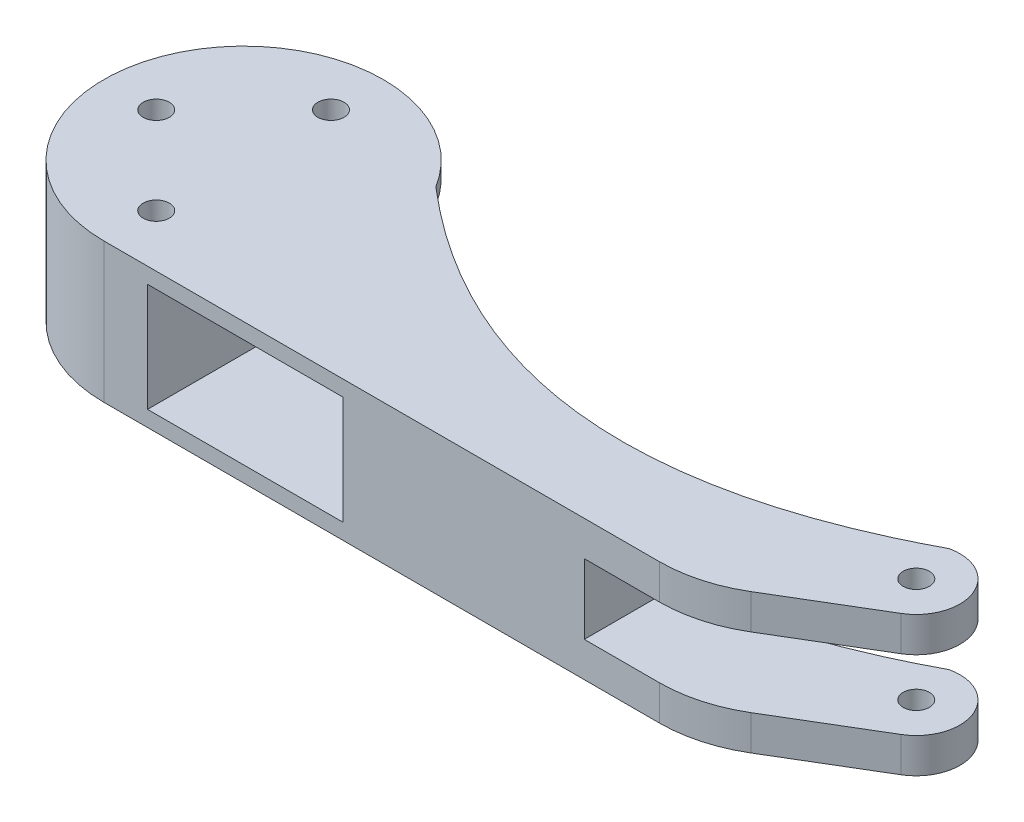
SolidWorks part; units mm, degrees
ref_plane "前视基准面" through (0, 0, 0) normal (0, 0, 1) x (1, 0, 0)
ref_plane "上视基准面" through (0, 0, 0) normal (0, 1, 0) x (1, 0, 0)
ref_plane "右视基准面" through (0, 0, 0) normal (1, 0, 0) x (0, 0, -1)
other "Configuration Table"
sketch "Sketch1" plane through (0, 0, 0) normal (0, 1, 0) x (1, 0, 0)
  line L0 (80, -3.5578) -> (80, -3)
  line L1 (0, -16) -> (80, -16)
  line L2 (80, -16) -> (80, -3)
  line L3 (45, -6) -> (45, -16)
  line L4 (45, -6) -> (7.5685, 14.0968)
  line L5 (45, -6) -> (78.8683, 1.8702)
  line L6 (68, -16) -> (82.5658, -7.2915)
  circle A0 centre (0, 0) radius 16
  circle A1 centre (80, -3) radius 1.5
  circle A2 centre (80, -3) radius 5
  spline S0 degree 2 poles (7.5685, 14.0968) (39.626, -19.032) (78.8683, 1.8702) knots 0 0 0 1 1 1
  point P9 (45, -6)
  point P12 (68, -16)
  dimension "D1" = 32
  dimension "D3" = 3
  dimension "D5" = 10
  dimension "D2" = 80
  dimension "D4" = 3
  dimension "D6" = 35
  dimension "D7" = 12
extrude "Boss-Extrude2" add sketch "Sketch1" along normal blind 16
fillet "Fillet1" radius 16 1 edges at (68, 8, 16)
sketch "Sketch2" plane through (0, 0, 16) normal (0, 0, 1) x (1, 0, 0)
  line L0 (85, 0) -> (55, 0) construction
  line L1 (0, 0) -> (63.5817, 0) construction
  line L2 (55, 0) -> (55, 16) construction
  line L3 (0, 16) -> (63.5817, 16) construction
  line L4 (85, 0) -> (85, 16) construction
  line L5 (55, 0) -> (55, 4) construction
  line L6 (55, 4) -> (55, 12) construction
  line L8 (55, 12) -> (85, 12)
  line L9 (55, 12) -> (55, 4)
  line L10 (55, 4) -> (85, 4)
  line L11 (85, 12) -> (85, 4)
  dimension "D1" = 30
  dimension "D2" = 4
  dimension "D3" = 8
extrude "Cut-Extrude2" cut sketch "Sketch2" against normal through all contours L10 L11 L8 L9
sketch "Sketch3" plane through (0, 0, 16) normal (0, 0, 1) x (1, 0, 0)
  line L0 (0, 16) -> (0, 0) construction
  line L1 (0, 16) -> (27.4, 16)
  line L2 (0, 16) -> (0, 14.2)
  line L3 (0, 14.2) -> (27.4, 14.2)
  line L4 (27.4, 16) -> (27.4, 14.2)
  line L5 (27.4, 14.2) -> (0, 14.2)
  line L6 (27.4, 14.2) -> (27.4, 1.8)
  line L7 (27.4, 1.8) -> (0, 1.8)
  line L8 (0, 14.2) -> (0, 1.8)
  line L10 (27.4, 1.8) -> (0, 1.8)
  line L11 (27.4, 1.8) -> (27.4, 0)
  line L12 (27.4, 0) -> (0, 0)
  line L13 (0, 1.8) -> (0, 0)
  line L14 (5, 14.2) -> (27.4, 14.2)
  line L15 (5, 14.2) -> (5, 1.8)
  line L16 (5, 1.8) -> (27.4, 1.8)
  line L17 (27.4, 14.2) -> (27.4, 1.8)
  dimension "D1" = 1.8
  dimension "D2" = 1.8
  dimension "D3" = 5
  dimension "D4" = 22.4
extrude "Cut-Extrude3" cut sketch "Sketch3" against normal through all contours L5 L15 L7 L6
sketch "Sketch4" plane through (0, 0, 0) normal (0, -1, 0) x (1, 0, 0)
  circle A0 centre (0, 0) radius 10
  circle A1 centre (0, -10) radius 1.5
  circle A2 centre (-10, 0) radius 1.5
  circle A3 centre (0, 10) radius 1.5
  circle A4 centre (10, 0) radius 1.5
  point P14 (0, 0)
  dimension "D1" = 20
  dimension "D2" = 3
  dimension "D3" = 4
extrude "Cut-Extrude4" cut sketch "Sketch4" against normal through all contours A1 | A2 | A3
